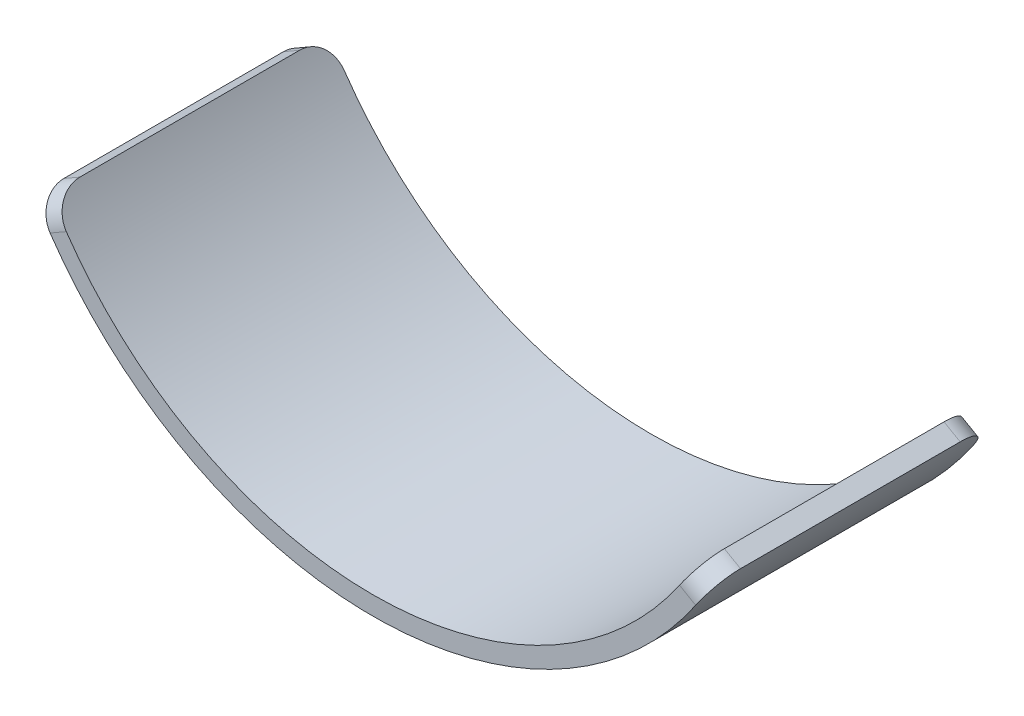
SolidWorks part; units mm, degrees
ref_plane "Front Plane" through (0, 0, 0) normal (0, 0, 1) x (1, 0, 0)
ref_plane "Top Plane" through (0, 0, 0) normal (0, 1, 0) x (1, 0, 0)
ref_plane "Right Plane" through (0, 0, 0) normal (1, 0, 0) x (0, 0, -1)
sketch "Sketch1" plane through (0, 0, 0) normal (0, 0, 1) x (1, 0, 0)
  line L0 (0, 330.9789) -> (0, -427.596) construction
  line L1 (0, 0) -> (-219.9705, -127) construction
  line L2 (0, 0) -> (220.1434, -126.7) construction
  line L3 (-219.9705, -127) -> (-230.969, -133.35)
  line L4 (231.1506, -133.035) -> (220.1434, -126.7)
  arc A0 (-219.9705, -127) -> (220.1434, -126.7) centre (0, 0) ccw
  arc A1 (-230.969, -133.35) -> (231.1506, -133.035) centre (0, 0) ccw
  dimension "D1" = 508
  dimension "D4" = 140
  dimension "D2" = 60
  dimension "D3" = 12.7
  dimension "D5" = 12.7
extrude "Boss-Extrude1" add sketch "Sketch1" along normal mid plane 190
fillet "Fillet1" radius 20 4 edges at (225.647, -129.8675, 95) (225.647, -129.8675, -95) (-225.4697, -130.175, 95) (-225.4697, -130.175, -95)
